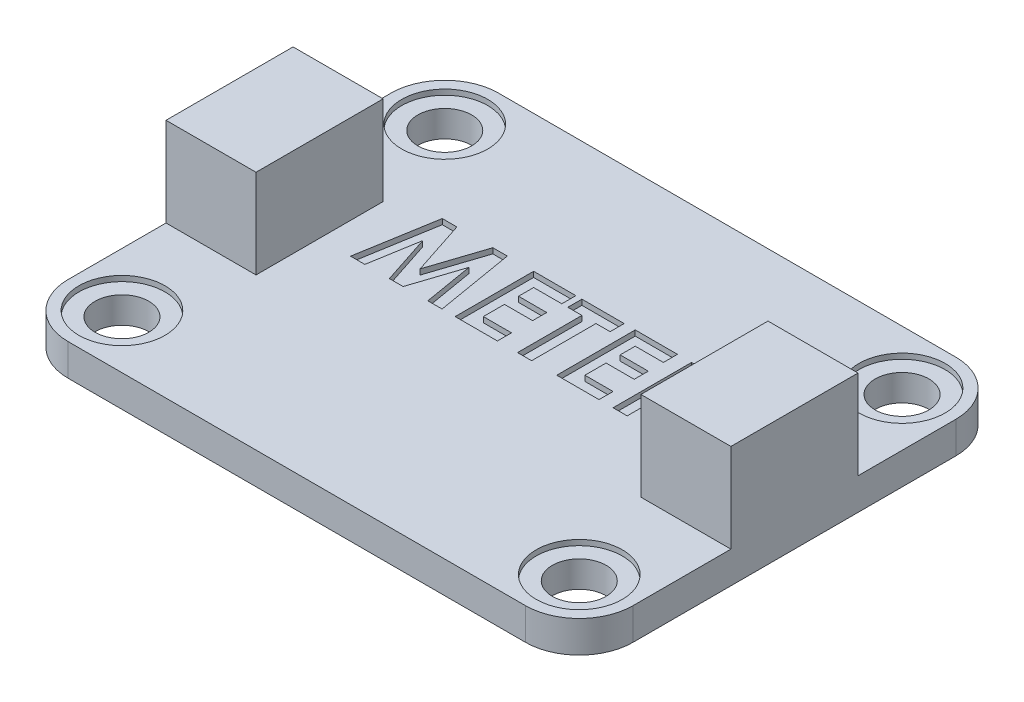
SolidWorks part; units mm, degrees
ref_plane "Front Plane" through (0, 0, 0) normal (0, 0, 1) x (1, 0, 0)
ref_plane "Top Plane" through (0, 0, 0) normal (0, 1, 0) x (1, 0, 0)
ref_plane "Right Plane" through (0, 0, 0) normal (1, 0, 0) x (0, 0, -1)
sketch "Sketch1" plane through (0, 0, 0) normal (0, 1, 0) x (1, 0, 0)
  line L1 (-13.335, -10.16) -> (13.335, -10.16)
  line L2 (-13.335, -10.16) -> (-13.335, 10.16)
  line L3 (-13.335, 10.16) -> (13.335, 10.16)
  line L4 (13.335, -10.16) -> (13.335, 10.16)
  line L5 (-13.335, -10.16) -> (13.335, 10.16) construction
  line L6 (-13.335, 10.16) -> (13.335, -10.16) construction
  point P0 (0, 0)
  dimension "D1" = 20.32
  dimension "D2" = 26.67
extrude "Boss-Extrude1" add sketch "Sketch1" along normal blind 1.5
sketch "Sketch2" plane through (0, 1.5, 0) normal (0, 1, 0) x (1, 0, 0)
  line L1 (-10.795, -7.62) -> (10.795, -7.62) construction
  line L2 (-10.795, -7.62) -> (-10.795, 7.62) construction
  line L3 (-10.795, 7.62) -> (10.795, 7.62) construction
  line L4 (10.795, -7.62) -> (10.795, 7.62) construction
  line L5 (-10.795, -7.62) -> (10.795, 7.62) construction
  line L6 (-10.795, 7.62) -> (10.795, -7.62) construction
  circle A0 centre (10.795, 7.62) radius 1.27
  circle A1 centre (-10.795, 7.62) radius 1.27
  circle A2 centre (-10.795, -7.62) radius 1.27
  circle A3 centre (10.795, -7.62) radius 1.27
  point P0 (0, 0)
  dimension "D3" = 2.54
  dimension "D1" = 21.59
  dimension "D2" = 15.24
extrude "Cut-Extrude1" cut sketch "Sketch2" against normal through all
fillet "Fillet1" radius 2.54 4 edges at (-13.335, 0.75, -10.16) (13.335, 0.75, -10.16) (13.335, 0.75, 10.16) (-13.335, 0.75, 10.16)
sketch "Sketch3" plane through (0, 1.5, 0) normal (0, 1, 0) x (1, 0, 0)
  line L0 (-13.335, 0) -> (13.335, 0) construction
  line L1 (13.335, -7.62) -> (13.335, 7.62) construction
  text T0 "<b>METER</b>" font "Century Gothic" height in points 14
  point P6 (0, 0)
extrude "Cut-Extrude2" cut sketch "Sketch3" against normal blind 0.254
sketch "Sketch4" plane through (0, 1.5, 0) normal (0, 1, 0) x (1, 0, 0)
  circle A0 centre (-10.795, 7.62) radius 2.032
  circle A1 centre (10.795, 7.62) radius 2.032
  circle A2 centre (10.795, -7.62) radius 2.032
  circle A3 centre (-10.795, -7.62) radius 2.032
  circle A4 centre (-10.795, -7.62) radius 1.27 construction
  circle A5 centre (10.795, -7.62) radius 1.27 construction
  circle A6 centre (10.795, 7.62) radius 1.27 construction
  circle A7 centre (-10.795, 7.62) radius 1.27 construction
  circle A8 centre (-10.795, -7.62) radius 1.27
  circle A9 centre (10.795, -7.62) radius 1.27
  circle A10 centre (10.795, 7.62) radius 1.27
  circle A11 centre (-10.795, 7.62) radius 1.27
  dimension "D1" = 4.064
extrude "Cut-Extrude3" cut sketch "Sketch4" against normal blind 0.254
sketch "Sketch5" plane through (0, 1.5, 0) normal (0, 1, 0) x (1, 0, 0)
  line L0 (-13.335, 0) -> (49986.665, 0) construction
  line L1 (-13.335, 7.62) -> (-13.335, -7.62) construction
  line L2 (13.335, -7.62) -> (13.335, 7.62) construction
  line L3 (-9.085, -3) -> (-13.335, -3)
  line L4 (-9.085, -3) -> (-9.085, 3)
  line L5 (-9.085, 3) -> (-13.335, 3)
  line L6 (-13.335, -3) -> (-13.335, 3)
  line L7 (-9.085, -3) -> (-13.335, 3) construction
  line L8 (-9.085, 3) -> (-13.335, -3) construction
  line L9 (9.085, -3) -> (13.335, -3)
  line L10 (9.085, -3) -> (9.085, 3)
  line L11 (9.085, 3) -> (13.335, 3)
  line L12 (13.335, -3) -> (13.335, 3)
  line L13 (9.085, -3) -> (13.335, 3) construction
  line L14 (9.085, 3) -> (13.335, -3) construction
  point P4 (-13.335, 0)
  point P5 (-11.21, 0)
  point P10 (11.21, 0)
  dimension "D1" = 6
  dimension "D2" = 4.25
extrude "Boss-Extrude3" add sketch "Sketch5" along normal blind 4.2
